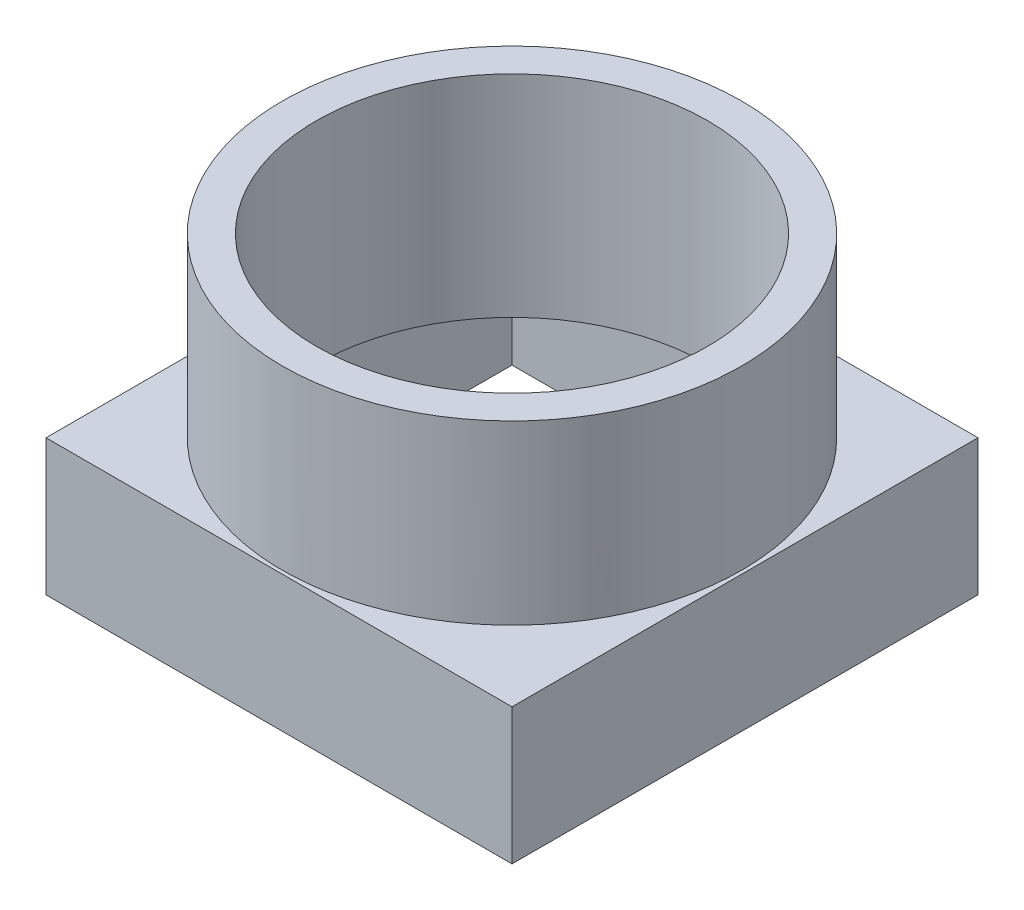
SolidWorks part; units mm, degrees
ref_plane "Front Plane" through (0, 0, 0) normal (0, 0, 1) x (1, 0, 0)
ref_plane "Top Plane" through (0, 0, 0) normal (0, 1, 0) x (1, 0, 0)
ref_plane "Right Plane" through (0, 0, 0) normal (1, 0, 0) x (0, 0, -1)
sketch "Sketch1" plane through (0, 0, 0) normal (0, 1, 0) x (1, 0, 0)
  line L0 (6.85, 6.85) -> (-6.85, -6.85) construction
  line L1 (-6.85, 6.85) -> (6.85, 6.85)
  line L2 (-6.85, 6.85) -> (-6.85, -6.85)
  line L3 (-6.85, -6.85) -> (6.85, -6.85)
  line L4 (6.85, 6.85) -> (6.85, -6.85)
  dimension "D1" = 13.7
  dimension "D2" = 13.7
extrude "Boss-Extrude1" add sketch "Sketch1" along normal blind 4 contours L4 L3 L2 L1
sketch "Sketch2" plane through (0, 0, 0) normal (0, 1, 0) x (1, 0, 0)
  circle A0 centre (0, 0) radius 6.75
  dimension "D1" = 13.5
extrude "Boss-Extrude2" add sketch "Sketch2" along normal blind 9.2
shell "Shell1" thickness 1
